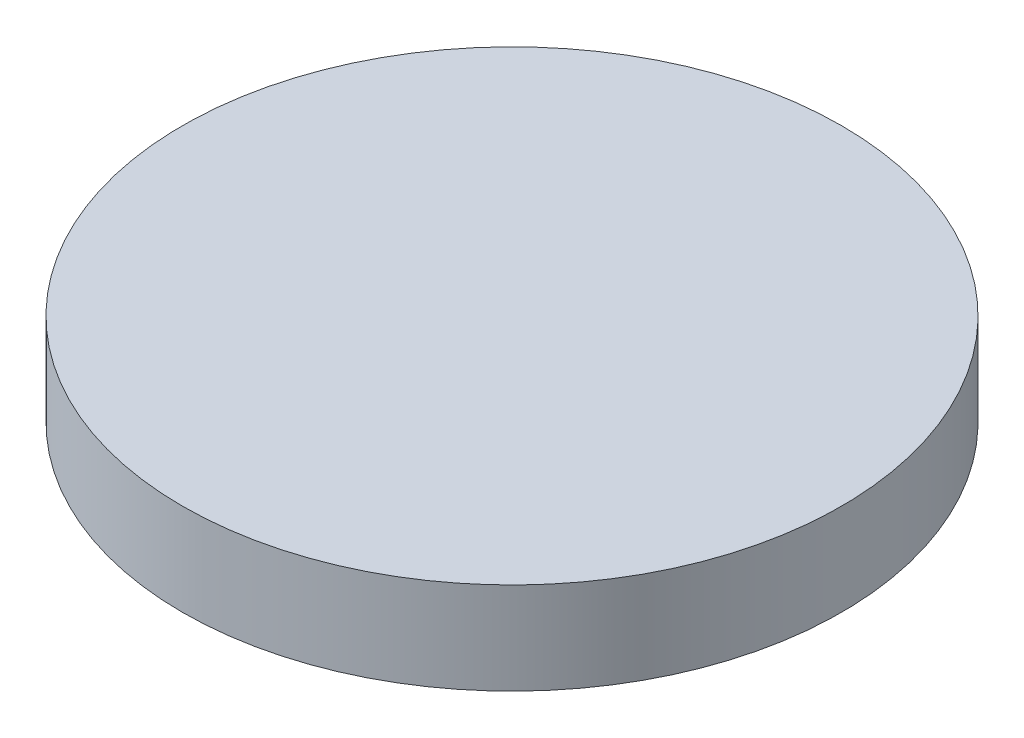
SolidWorks part; units mm, degrees
ref_plane "Front Plane" through (0, 0, 0) normal (0, 0, 1) x (1, 0, 0)
ref_plane "Top Plane" through (0, 0, 0) normal (0, 1, 0) x (1, 0, 0)
ref_plane "Right Plane" through (0, 0, 0) normal (1, 0, 0) x (0, 0, -1)
sketch "Sketch1" plane through (0, 0, 0) normal (0, 1, 0) x (1, 0, 0)
  circle A0 centre (0, 0) radius 27.305
  dimension "D1" = 54.61
extrude "Boss-Extrude1" add sketch "Sketch1" along normal blind 7.62 contours A0
